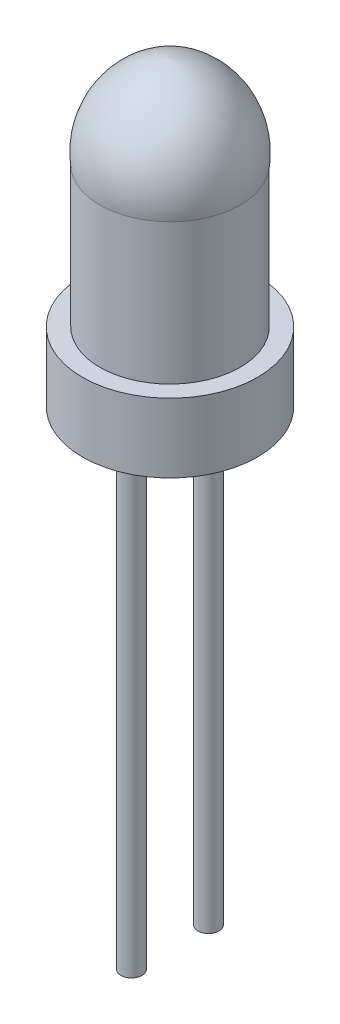
SolidWorks part; units mm, degrees
ref_plane "Front Plane" through (0, 0, 0) normal (0, 0, 1) x (1, 0, 0)
ref_plane "Top Plane" through (0, 0, 0) normal (0, 1, 0) x (1, 0, 0)
ref_plane "Right Plane" through (0, 0, 0) normal (1, 0, 0) x (0, 0, -1)
sketch "Sketch1" plane through (0, 0, 0) normal (0, 0, 1) x (1, 0, 0)
  line L0 (0, 0) -> (0, 6.4226)
  line L1 (0, 0) -> (1.87, 0)
  line L2 (1.87, 0) -> (1.87, 1.4753)
  line L3 (1.87, 1.4753) -> (1.5, 1.4753)
  line L4 (1.5, 1.4753) -> (1.5, 4.4753)
  arc A2 (0, 6.4226) -> (1.5, 4.4753) centre (-0.2236, 4.6989) cw
  dimension "D1" = 3
  dimension "D2" = 1.4753
  dimension "D3" = 1.87
  dimension "D4" = 1.5
revolve "Revolve1" add sketch "Sketch1" angle 360 about L0
sketch "Sketch2" plane through (0, 0, 0) normal (0, -1, 0) x (-1, 0, 0)
  line L0 (0, 0) -> (2.1801, 0) construction
  circle A0 centre (0, 0.8223) radius 0.2251
  circle A1 centre (0, -0.8223) radius 0.2251
extrude "Boss-Extrude1" add sketch "Sketch2" along normal blind 10
